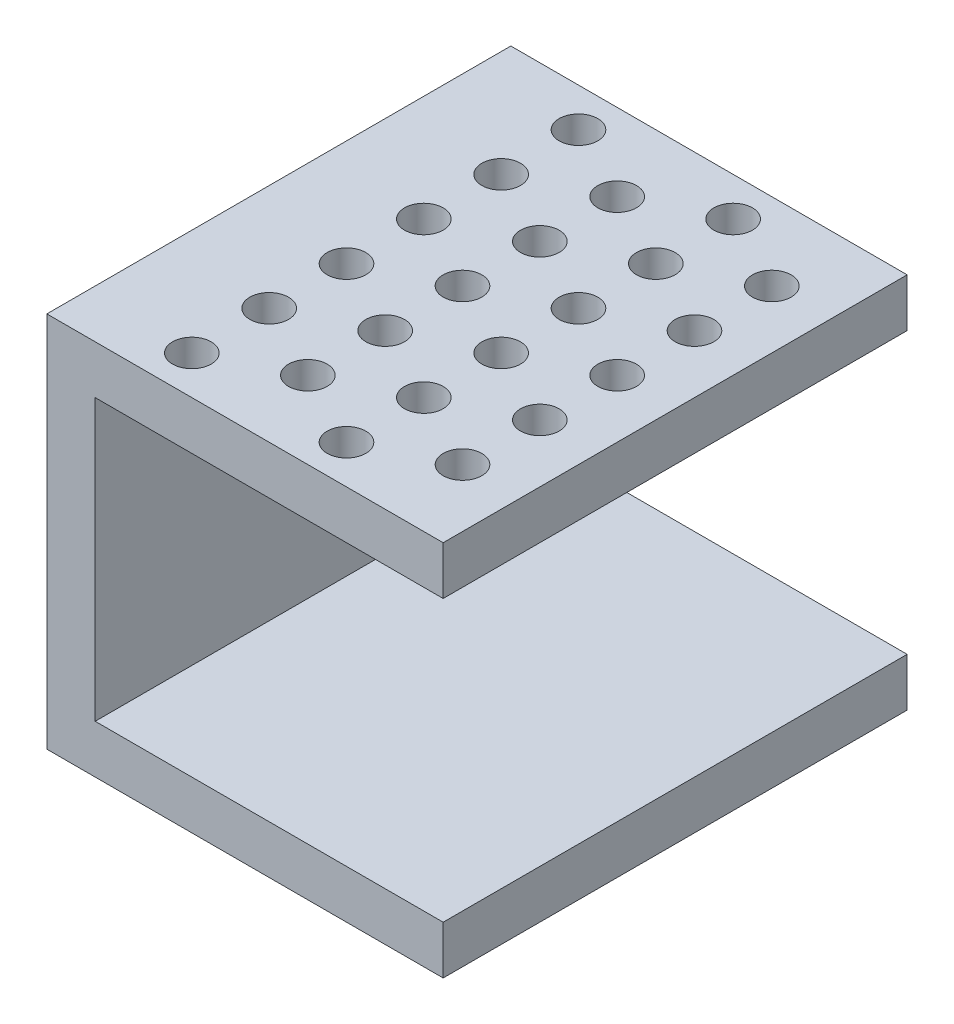
SolidWorks part; units mm, degrees
ref_plane "Front Plane" through (0, 0, 0) normal (0, 0, 1) x (1, 0, 0)
ref_plane "Top Plane" through (0, 0, 0) normal (0, 1, 0) x (1, 0, 0)
ref_plane "Right Plane" through (0, 0, 0) normal (1, 0, 0) x (0, 0, -1)
sketch "Sketch2" plane through (0, 0, 0) normal (0, 1, 0) x (1, 0, 0)
  line L1 (-20, 16) -> (-2, 16)
  line L2 (-20, 16) -> (-20, -8)
  line L3 (-20, -8) -> (-2, -8)
  line L4 (-2, 16) -> (-2, -8)
  circle A0 centre (-17, -6) radius 1
  circle A1 centre (-17, -2) radius 1
  circle A2 centre (-17, 2) radius 1
  circle A3 centre (-17, 6) radius 1
  circle A4 centre (-17, 10) radius 1
  circle A5 centre (-17, 14) radius 1
  circle A6 centre (-13, -4) radius 1
  circle A7 centre (-13, 0) radius 1
  circle A8 centre (-13, 4) radius 1
  circle A9 centre (-13, 8) radius 1
  circle A10 centre (-13, 12) radius 1
  circle A11 centre (-9, -6) radius 1
  circle A12 centre (-9, -2) radius 1
  circle A13 centre (-9, 2) radius 1
  circle A14 centre (-9, 6) radius 1
  circle A15 centre (-9, 10) radius 1
  circle A16 centre (-9, 14) radius 1
  circle A17 centre (-5, -4) radius 1
  circle A18 centre (-5, 0) radius 1
  circle A19 centre (-5, 4) radius 1
  circle A20 centre (-5, 8) radius 1
  circle A21 centre (-5, 12) radius 1
  point P8 (-18, -4)
  point P9 (-18, -3)
  point P10 (-18, -2)
  point P11 (0, 0)
  point P12 (-18, 2)
  point P13 (0, 0)
  point P14 (-18, -2)
  point P15 (-18, 2)
  point P16 (-18, -2)
  point P19 (-18, 2)
  point P26 (-18, 6)
  point P27 (-18, 10)
  point P28 (-18, 14)
  point P31 (-16, -4)
  point P40 (-16, 12)
  point P41 (-16, 8)
  point P42 (-16, 4)
  point P43 (-16, 0)
  point P44 (-16, -4)
  point P45 (-14, 8)
  point P46 (-14, 12)
  point P47 (-14, 4)
  point P48 (-14, 0)
  point P49 (-14, -4)
  point P72 (-10, 14)
  point P73 (-10, 10)
  point P74 (-10, 6)
  point P75 (-10, 2)
  point P76 (-10, -2)
  point P77 (-10, -6)
  point P78 (-6, -4)
  point P79 (-6, 0)
  point P80 (-6, 4)
  point P81 (-6, 8)
  point P82 (-6, 12)
  point P83 (-17, 14)
  point P84 (-17, 10)
  point P85 (-17, 6)
  point P86 (-17, 2)
  point P87 (-17, -2)
  point P88 (-17, -6)
  point P89 (-13, 0)
  point P90 (-13, -4)
  point P91 (-13, 4)
  point P92 (-13, 8)
  point P93 (-13, 12)
  point P94 (-9, 10)
  point P95 (-9, 14)
  point P96 (-9, 6)
  point P97 (-9, 2)
  point P98 (-9, -2)
  point P99 (-9, -6)
  point P100 (-5, -4)
  point P101 (-5, 0)
  point P102 (-5, 4)
  point P103 (-5, 8)
  point P104 (-5, 12)
  dimension "D1" = 24
  dimension "D2" = 18
extrude "Boss-Extrude2" add sketch "Sketch2" along normal blind 2.5
sketch "Sketch4" plane through (-20, 0, 0) normal (-1, 0, 0) x (0, 0, 1)
  line L1 (-16, 0) -> (8, 0)
  line L2 (-16, 0) -> (-16, 2.5)
  line L3 (-16, 2.5) -> (8, 2.5)
  line L4 (8, 0) -> (8, 2.5)
extrude "Boss-Extrude3" add sketch "Sketch4" along normal blind 2.5
sketch "Sketch6" plane through (0, 0, 0) normal (0, -1, 0) x (1, 0, 0)
  line L5 (-2, -16) -> (-22.5, -16) construction
  line L6 (-22.5, 8) -> (-2, 8) construction
  line L8 (-20, -16) -> (-20, 8) construction
  line L9 (-22.5, -16) -> (-22.5, 8) construction
  line L15 (-22.5, 8) -> (-20, 8)
  line L16 (-22.5, 8) -> (-22.5, -16)
  line L17 (-22.5, -16) -> (-20, -16)
  line L18 (-20, 8) -> (-20, -16)
  dimension "D2" = 2.5
extrude "Boss-Extrude5" add sketch "Sketch6" along normal blind 17
sketch "Sketch7" plane through (-20, 0, 0) normal (1, 0, 0) x (0, 0, -1)
  line L0 (16, -17) -> (16, 0) construction
  line L1 (-8, -17) -> (16, -17)
  line L2 (-8, -17) -> (-8, -14.5)
  line L3 (-8, -14.5) -> (16, -14.5)
  line L4 (16, -17) -> (16, -14.5)
  dimension "D1" = 2.5
extrude "Boss-Extrude6" add sketch "Sketch7" along normal blind 18
